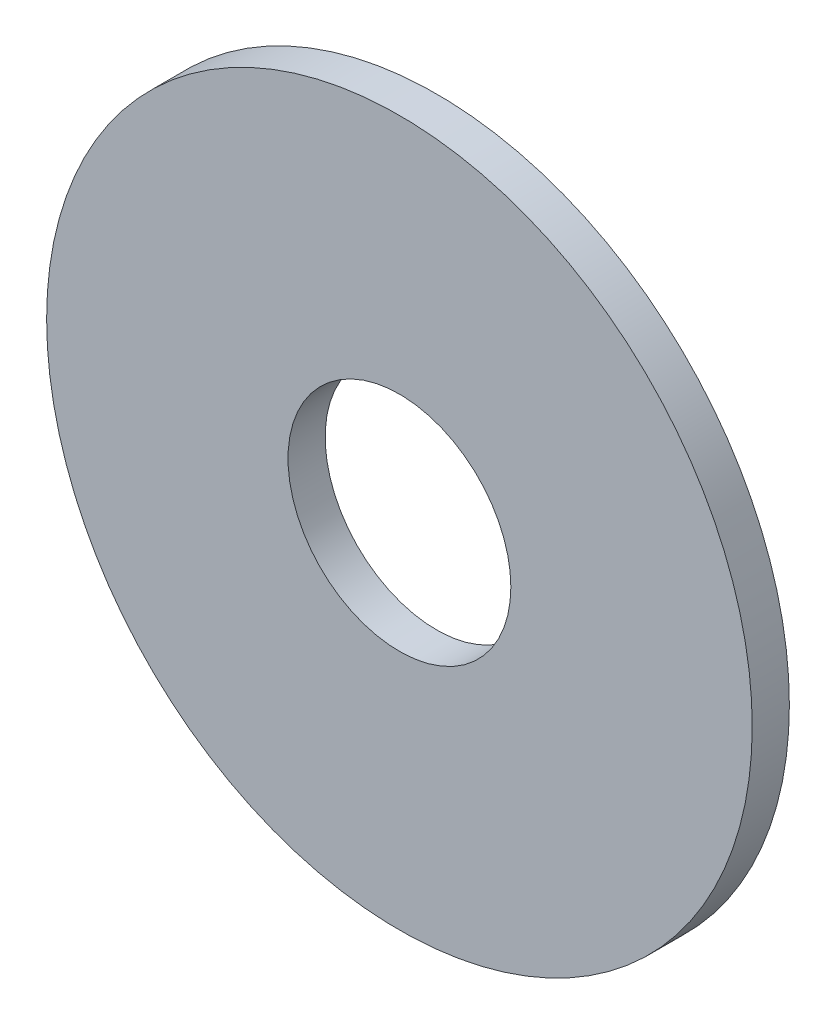
SolidWorks part; units mm, degrees
material "6061 合金"
ref_plane "前视基准面" through (0, 0, 0) normal (0, 0, 1) x (1, 0, 0)
ref_plane "上视基准面" through (0, 0, 0) normal (0, 1, 0) x (1, 0, 0)
ref_plane "右视基准面" through (0, 0, 0) normal (1, 0, 0) x (0, 0, -1)
other "Configuration Table"
sketch "草图1" plane through (0, 0, 0) normal (0, 0, 1) x (1, 0, 0)
  circle A0 centre (0, 0) radius 9.5
  circle A1 centre (0, 0) radius 3
  dimension "D1" = 19
  dimension "D2" = 6
extrude "凸台-拉伸1" add sketch "草图1" along normal blind 1
